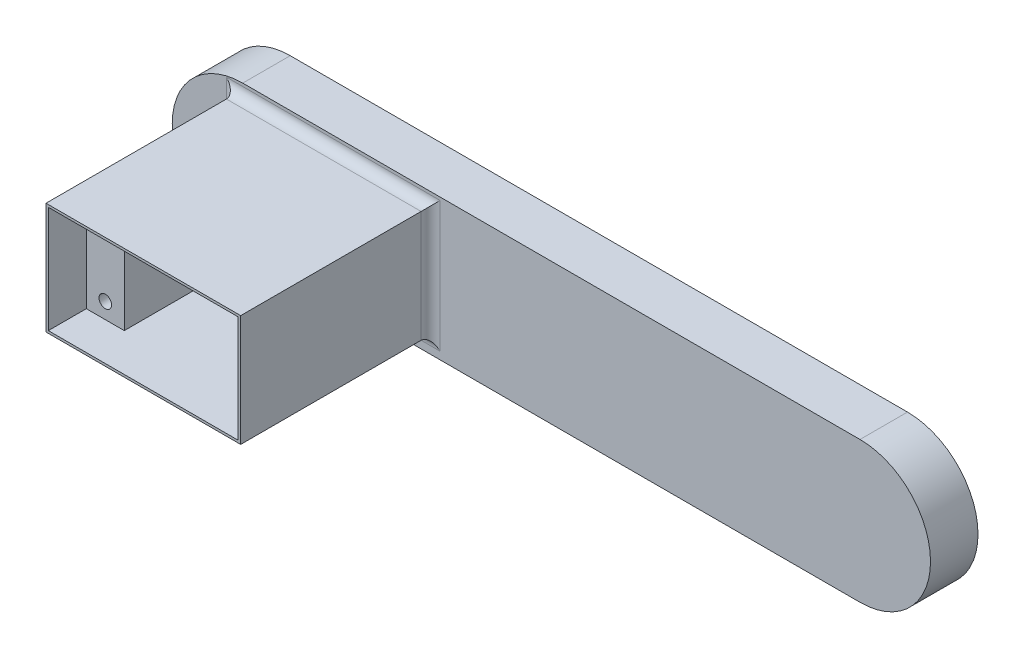
SolidWorks part; units mm, degrees
ref_plane "Front Plane" through (0, 0, 0) normal (0, 0, 1) x (1, 0, 0)
ref_plane "Top Plane" through (0, 0, 0) normal (0, 1, 0) x (1, 0, 0)
ref_plane "Right Plane" through (0, 0, 0) normal (1, 0, 0) x (0, 0, -1)
sketch "Sketch1" plane through (0, 0, 0) normal (0, 0, 1) x (1, 0, 0)
  line L0 (-63.6567, -4.0299) -> (66.3433, -4.0299) construction
  line L5 (-63.6567, 10.8209) -> (66.3433, 10.8209)
  line L6 (-63.6567, -18.8806) -> (66.3433, -18.8806)
  arc A0 (-63.6567, 10.8209) -> (-63.6567, -18.8806) centre (-63.6567, -4.0299) ccw
  arc A1 (66.3433, -18.8806) -> (66.3433, 10.8209) centre (66.3433, -4.0299) ccw
  point P6 (1.3433, -4.0299)
extrude "Boss-Extrude1" add sketch "Sketch1" along normal blind 10
sketch "Sketch2" plane through (0, 0, 0) normal (0, 0, -1) x (-1, 0, 0)
  line L0 (-81.194, -4.0299) -> (-66.3433, -4.0299) construction
  arc A0 (-66.3433, 10.8209) -> (-66.3433, -18.8806) centre (-66.3433, -4.0299) ccw construction
  circle A1 centre (-66.3433, -4.0299) radius 3.25
  dimension "D1" = 6.5
extrude "Cut-Extrude1" cut sketch "Sketch2" against normal blind 6
sketch "Sketch3" plane through (0, 0, 10) normal (0, 0, 1) x (1, 0, 0)
  line L1 (-64.603, 7.6997) -> (-24.603, 7.6997)
  line L2 (-64.603, 7.6997) -> (-64.603, -14.8003)
  line L3 (-64.603, -14.8003) -> (-24.603, -14.8003)
  line L4 (-24.603, 7.6997) -> (-24.603, -14.8003)
  line L5 (-65.0923, 8.1955) -> (-24.0923, 8.1955)
  line L6 (-65.0923, 8.1955) -> (-65.0923, -15.3045)
  line L7 (-65.0923, -15.3045) -> (-24.0923, -15.3045)
  line L8 (-24.0923, 8.1955) -> (-24.0923, -15.3045)
  dimension "D1" = 40
  dimension "D2" = 22.5
  dimension "D3" = 41
  dimension "D4" = 23.5
extrude "Boss-Extrude3" add sketch "Sketch3" along normal blind 40
sketch "Sketch4" plane through (0, 0, 10) normal (0, 0, 1) x (1, 0, 0)
  line L0 (-64.603, -14.8003) -> (-24.603, -14.8003) construction
  line L1 (-64.603, 7.6997) -> (-56.6059, 7.6997)
  line L2 (-64.603, 7.6997) -> (-64.603, -14.8003)
  line L3 (-64.603, -14.8003) -> (-56.6059, -14.8003)
  line L4 (-56.6059, 7.6997) -> (-56.6059, -14.8003)
  line L5 (-64.603, -14.8003) -> (-24.603, -14.8003) construction
  line L6 (-24.603, 7.6997) -> (-32.6041, 7.6997)
  line L7 (-24.603, 7.6997) -> (-24.603, -14.8003)
  line L8 (-24.603, -14.8003) -> (-32.6041, -14.8003)
  line L9 (-32.6041, 7.6997) -> (-32.6041, -14.8003)
extrude "Boss-Extrude4" add sketch "Sketch4" along normal blind 32
sketch "Sketch5" plane through (0, 0, 42) normal (0, 0, 1) x (1, 0, 0)
  line L0 (-64.603, -3.5503) -> (-24.603, -3.5503) construction
  line L1 (-64.603, 7.6997) -> (-64.603, -14.8003) construction
  line L2 (-24.603, -14.8003) -> (-24.603, 7.6997) construction
  line L3 (-28.6036, 7.6997) -> (-28.6036, -14.8003) construction
  line L4 (-24.603, 7.6997) -> (-32.6041, 7.6997) construction
  line L5 (-32.6041, -14.8003) -> (-24.603, -14.8003) construction
  line L6 (-60.6044, 7.6997) -> (-60.6044, -14.8003) construction
  line L7 (-56.6059, 7.6997) -> (-64.603, 7.6997) construction
  line L8 (-64.603, -14.8003) -> (-56.6059, -14.8003) construction
  line L9 (-44.605, 7.6997) -> (-60.6044, 3.8069) construction
  line L10 (-32.6041, 7.6997) -> (-56.6059, 7.6997) construction
  line L11 (-60.6044, 3.8069) -> (-28.6036, 3.8069) construction
  line L12 (-28.6036, 3.8069) -> (-60.6044, -11.4712) construction
  line L13 (-60.6044, -11.4712) -> (-28.6036, -11.4712) construction
  circle A0 centre (-60.6044, 3.8069) radius 1.2618
  circle A1 centre (-28.6036, 3.8069) radius 1.302
  circle A2 centre (-60.6044, -11.4712) radius 1.3193
  circle A3 centre (-28.6036, -11.4712) radius 1.31
extrude "Cut-Extrude2" cut sketch "Sketch5" against normal blind 6
fillet "Fillet1" radius 2 5 edges at (-44.605, 7.6997, 10) (-44.5923, 8.1955, 10) (-65.0923, -3.5545, 10) (-44.5923, -15.3045, 10) (-24.0923, -3.5545, 10)
